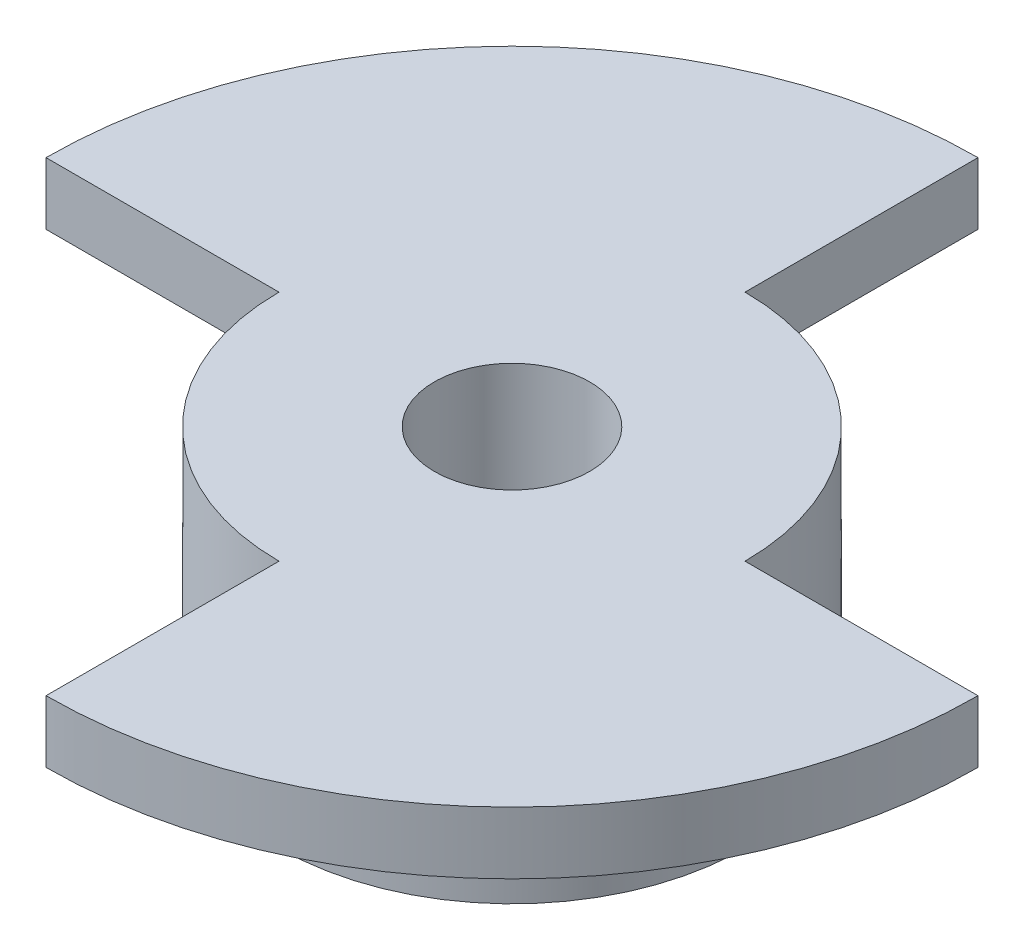
SolidWorks part; units mm, degrees
material "1060 Alloy"
ref_plane "Front Plane" through (0, 0, 0) normal (0, 0, 1) x (1, 0, 0)
ref_plane "Top Plane" through (0, 0, 0) normal (0, 1, 0) x (1, 0, 0)
ref_plane "Right Plane" through (0, 0, 0) normal (1, 0, 0) x (0, 0, -1)
sketch "Sketch1" plane through (0, 0, 0) normal (0, 0, 1) x (1, 0, 0)
  line L0 (2.5, 0) -> (7.5, 0)
  line L1 (7.5, 0) -> (7.5, 6)
  line L2 (7.5, 6) -> (15, 6)
  line L3 (15, 6) -> (15, 8)
  line L4 (15, 8) -> (2.5, 8)
  line L5 (0, 24.6429) -> (0, 0) construction
  line L6 (2.5, 0) -> (2.5, 8)
  dimension "D1" = 5
  dimension "D2" = 15
  dimension "D3" = 2
  dimension "D4" = 8
  dimension "D5" = 30
revolve "Revolve1" add sketch "Sketch1" angle 360 about L5
sketch "Sketch2" plane through (0, 6, 0) normal (0, -1, 0) x (1, 0, 0)
  line L0 (0, 7.5) -> (0, 23.4871)
  line L1 (0, 23.4871) -> (-23.4871, 0)
  line L2 (-23.4871, 0) -> (-7.5, 0)
  line L3 (7.5, 0) -> (23.2355, 0)
  line L4 (23.2355, 0) -> (0, -21.9448)
  line L5 (0, -21.9448) -> (0, -7.5)
  circle A0 centre (0, 0) radius 7.5 construction
  circle A1 centre (0, 0) radius 7.5 construction
  arc A2 (0, -7.5) -> (7.5, 0) centre (0, 0) ccw
  arc A3 (0, 7.5) -> (-7.5, 0) centre (0, 0) ccw
extrude "Cut-Extrude1" cut sketch "Sketch2" against normal through all
